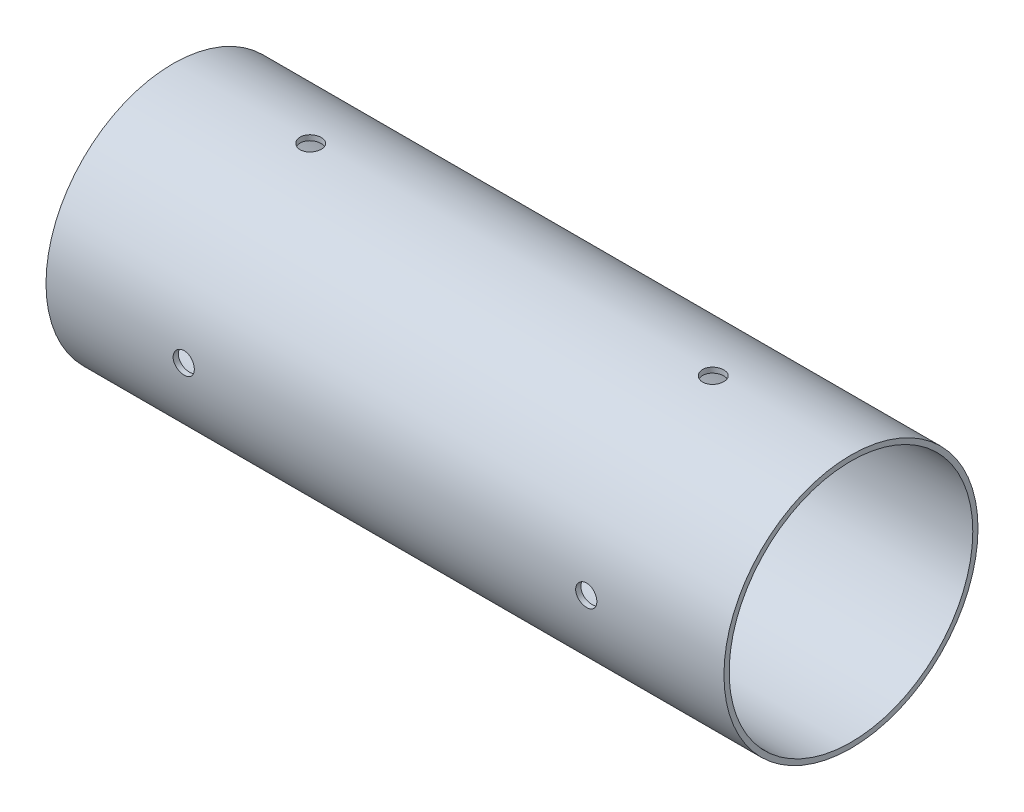
SolidWorks part; units mm, degrees
ref_plane "Front Plane" through (0, 0, 0) normal (1, 0, 0) x (0, 1, 0)
ref_plane "Top Plane" through (0, 0, 0) normal (0, 0, 1) x (0, 1, 0)
ref_plane "Right Plane" through (0, 0, 0) normal (0, 1, 0) x (-1, 0, 0)
sketch "Sketch1" plane through (0, 0, 0) normal (1, 0, 0) x (0, 1, 0)
  circle A0 centre (0, 0) radius 38.0746
  circle A1 centre (0, 0) radius 36.5125
  dimension "D1" = 73.025
  dimension "D2" = 76.1492
extrude "Boss-Extrude1" add sketch "Sketch1" along normal blind 203.2
sketch "Sketch2" plane through (0, 0, 0) normal (0, 1, 0) x (-1, 0, 0)
  circle A0 centre (-41.275, 0) radius 3.175
  point P7 (0, 0)
  dimension "D1" = 6.35
  dimension "D2" = 41.275
extrude "Cut-Extrude1" cut sketch "Sketch2" along normal through all
pattern_circular "CirPattern1" count 4 over 360 about axis through (203.2, 0, 0) along (-1, 0, 0) of "Cut-Extrude1"
sketch "Sketch3" plane through (0, 0, 0) normal (0, 1, 0) x (-1, 0, 0)
  line L0 (-203.2, 38.0746) -> (-203.2, -38.0746) construction
  circle A0 centre (-161.925, 0) radius 3.175
  point P4 (0, 0)
  dimension "D1" = 6.35
  dimension "D2" = 41.275
extrude "Cut-Extrude2" cut sketch "Sketch3" along normal through all
pattern_circular "CirPattern2" count 4 over 360 about axis through (203.2, 0, 0) along (-1, 0, 0) of "Cut-Extrude2"
